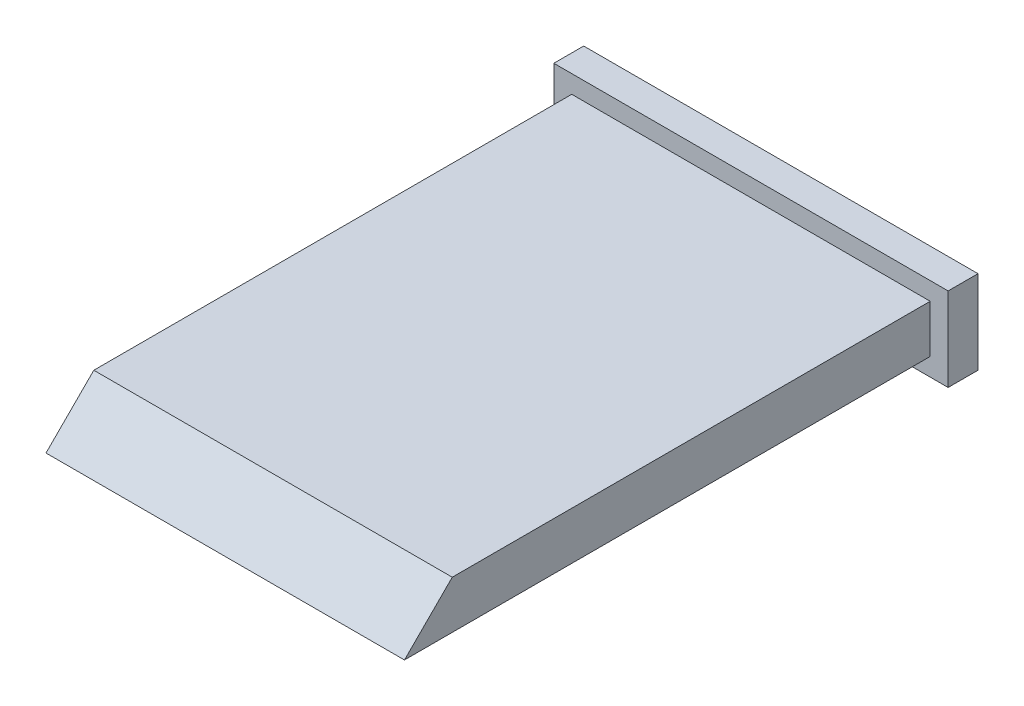
SolidWorks part; units mm, degrees
ref_plane "Front Plane" through (0, 0, 0) normal (0, 0, 1) x (1, 0, 0)
ref_plane "Top Plane" through (0, 0, 0) normal (0, 1, 0) x (1, 0, 0)
ref_plane "Right Plane" through (0, 0, 0) normal (1, 0, 0) x (0, 0, -1)
sketch "Sketch1" plane through (0, 0, 0) normal (1, 0, 0) x (0, 0, -1)
  line L0 (0, 0) -> (8, 8)
  line L1 (8, 8) -> (88, 8)
  line L2 (88, 8) -> (88, 0)
  line L3 (88, 0) -> (0, 0)
  dimension "D1" = 8
  dimension "D2" = 45
  dimension "D3" = 80
extrude "Boss-Extrude1" add sketch "Sketch1" along normal blind 60
sketch "Sketch3" plane through (0, 0, -88) normal (0, 0, -1) x (-1, 0, 0)
  line L8 (3, -3) -> (3, 11)
  line L9 (3, 11) -> (-63, 11)
  line L10 (-63, 11) -> (-63, -3)
  line L11 (-63, -3) -> (3, -3)
  line L12 (3, -3) -> (3, 11)
  line L13 (3, 11) -> (-63, 11)
  line L14 (-63, 11) -> (-63, -3)
  line L15 (-63, -3) -> (3, -3)
  dimension "D1" = 3
extrude "Boss-Extrude2" add sketch "Sketch3" along normal blind 5
